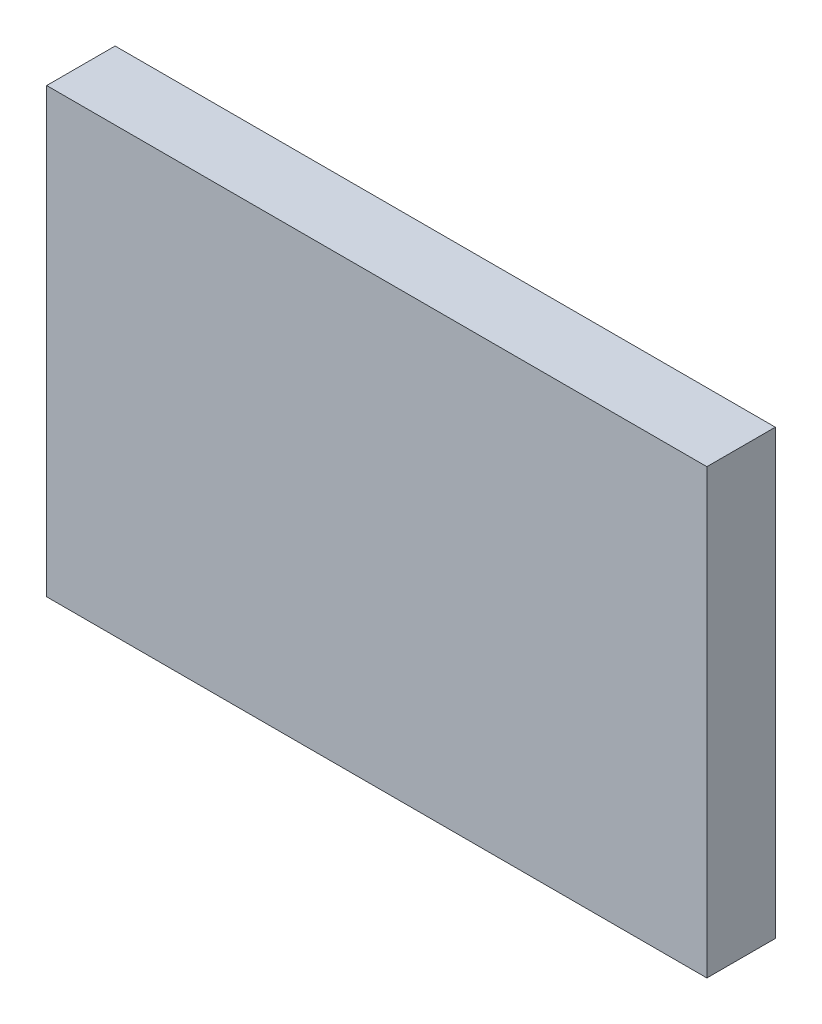
SolidWorks part; units mm, degrees
ref_plane "Plan de face" through (0, 0, 0) normal (0, 0, 1) x (1, 0, 0)
ref_plane "Plan de dessus" through (0, 0, 0) normal (0, 1, 0) x (1, 0, 0)
ref_plane "Plan de droite" through (0, 0, 0) normal (1, 0, 0) x (0, 0, -1)
sketch "Esquisse1" plane through (0, 0, 0) normal (0, 0, 1) x (1, 0, 0)
  line L1 (-36.9685, 19.8457) -> (45.0315, 19.8457)
  line L2 (-36.9685, 19.8457) -> (-36.9685, -35.1543)
  line L3 (-36.9685, -35.1543) -> (45.0315, -35.1543)
  line L4 (45.0315, 19.8457) -> (45.0315, -35.1543)
  dimension "D1" = 82
  dimension "D2" = 55
extrude "Boss.-Extru.1" add sketch "Esquisse1" along normal blind 8.5
